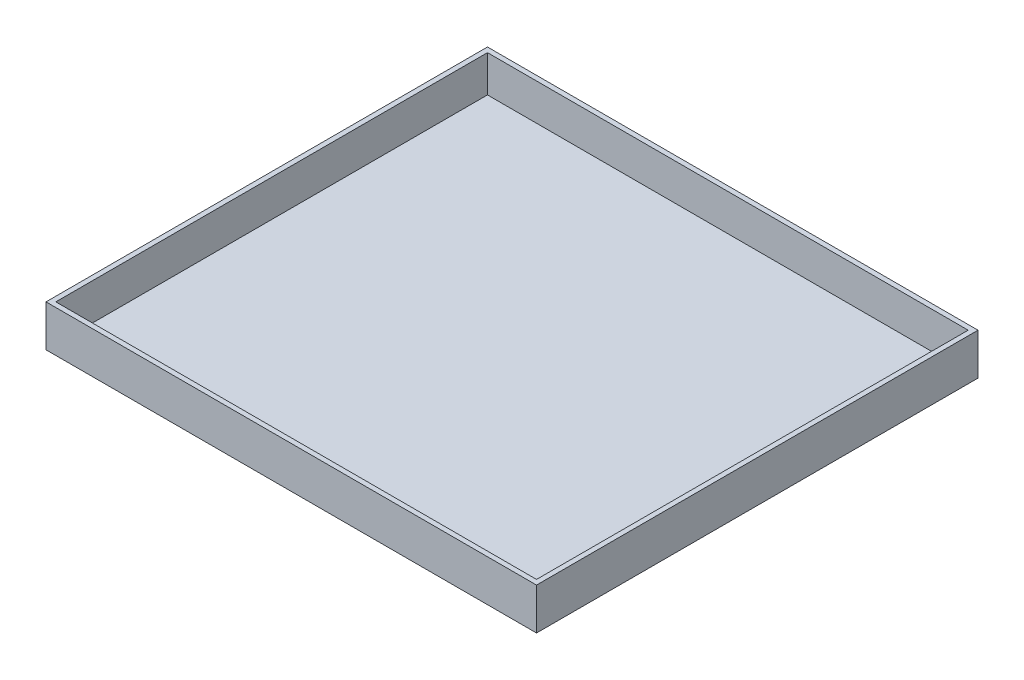
SolidWorks part; units mm, degrees
ref_plane "Alzado" through (0, 0, 0) normal (0, 0, 1) x (1, 0, 0)
ref_plane "Planta" through (0, 0, 0) normal (0, 1, 0) x (1, 0, 0)
ref_plane "Vista lateral" through (0, 0, 0) normal (1, 0, 0) x (0, 0, -1)
sketch "Croquis1" plane through (0, 0, 0) normal (0, 1, 0) x (1, 0, 0)
  line L1 (150, -135) -> (-150, -135)
  line L2 (150, -135) -> (150, 135)
  line L3 (150, 135) -> (-150, 135)
  line L4 (-150, -135) -> (-150, 135)
  line L5 (150, -135) -> (-150, 135) construction
  line L6 (150, 135) -> (-150, -135) construction
  point P0 (0, 0)
  dimension "D1" = 270
  dimension "D2" = 300
extrude "Saliente-Extruir1" add sketch "Croquis1" along normal blind 25.4
shell "Vaciado1" thickness 3
